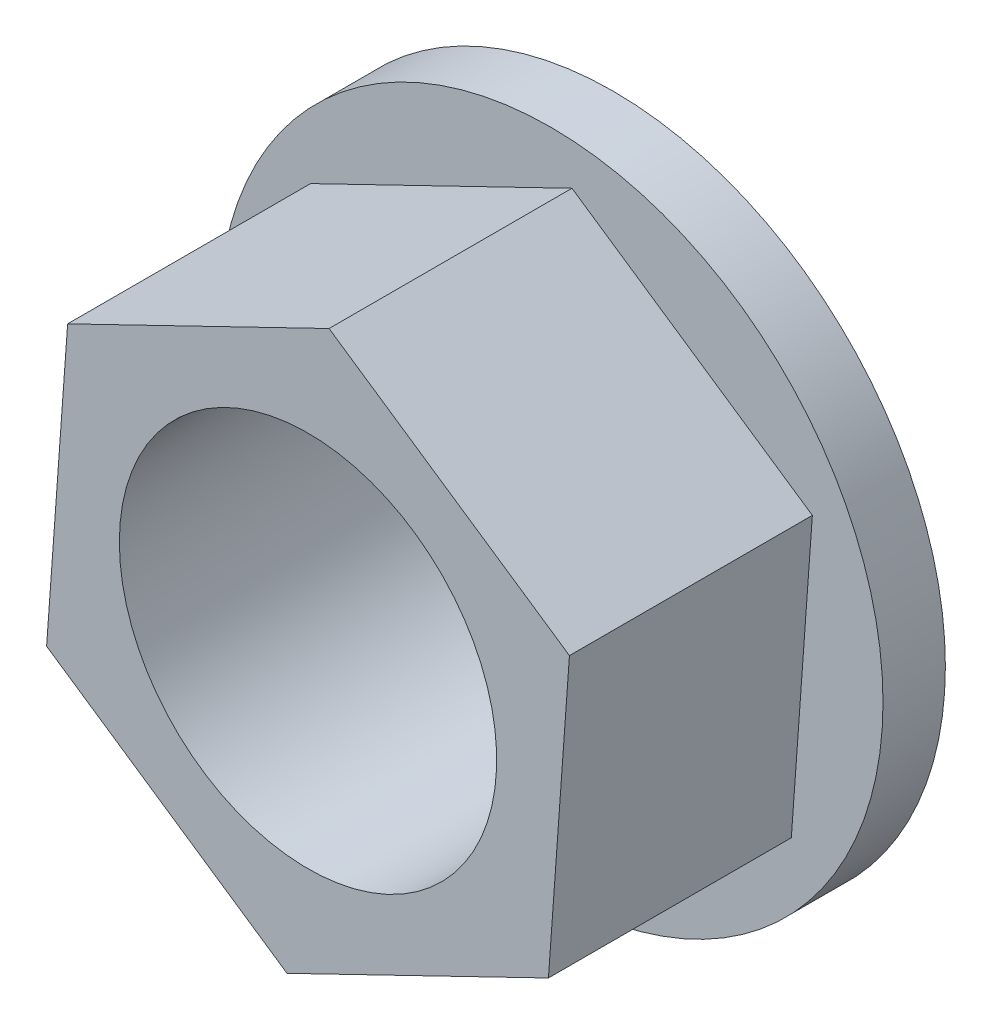
SolidWorks part; units mm, degrees
material "Plain Carbon Steel"
ref_plane "Front Plane" through (0, 0, 0) normal (0, 0, 1) x (1, 0, 0)
ref_plane "Top Plane" through (0, 0, 0) normal (0, 1, 0) x (1, 0, 0)
ref_plane "Right Plane" through (0, 0, 0) normal (1, 0, 0) x (0, 0, -1)
sketch "Sketch1" plane through (0, 0, 0) normal (0, 0, 1) x (1, 0, 0)
  circle A0 centre (0, 0) radius 4.191
  dimension "D1" = 8.382
extrude "Extrude1" add sketch "Sketch1" along normal blind 0.7874
sketch "Sketch2" plane through (0, 0, 0) normal (0, 0, 1) x (1, 0, 0)
  line L1 (-0.2653, -3.6566) -> (3.034, -2.058)
  line L2 (3.034, -2.058) -> (3.2993, 1.5985)
  line L3 (3.2993, 1.5985) -> (0.2653, 3.6566)
  line L4 (0.2653, 3.6566) -> (-3.034, 2.058)
  line L5 (-3.034, 2.058) -> (-3.2993, -1.5985)
  line L6 (-3.2993, -1.5985) -> (-0.2653, -3.6566)
  circle A0 centre (0, 0) radius 3.175 construction
  dimension "D1" = 6.35
extrude "Extrude2" add sketch "Sketch2" along normal blind 3.8532
sketch "Sketch3" plane through (0, 0, 0) normal (0, 0, -1) x (-1, 0, 0)
  circle A0 centre (0, 0) radius 2.3813
  dimension "D1" = 4.7625
extrude "Extrude3" cut sketch "Sketch3" against normal through all
